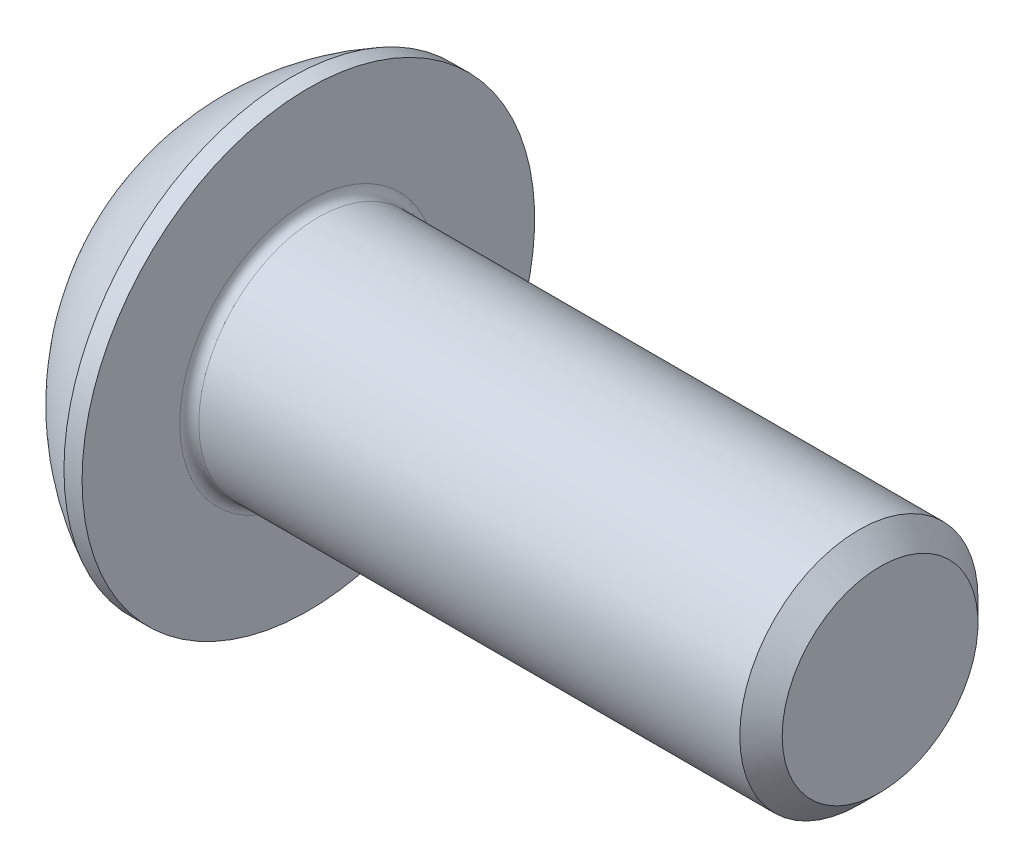
SolidWorks part; units mm, degrees
ref_plane "Plane1" through (0, 0, 0) normal (0, 0, 1) x (1, 0, 0)
ref_plane "Plane2" through (0, 0, 0) normal (0, 1, 0) x (1, 0, 0)
ref_plane "Plane3" through (0, 0, 0) normal (1, 0, 0) x (0, 0, -1)
other "Configuration Table"
sketch "BodySke" plane through (0, 0, 0) normal (0, 0, 1) x (1, 0, 0)
  line L0 (14.75, 0) -> (14.75, 2.055)
  line L1 (14.305, 2.5) -> (2.75, 2.5)
  line L2 (2.75, 2.5) -> (2.75, 4.75)
  line L3 (2.75, 4.75) -> (2.37, 4.75)
  line L4 (0, 0) -> (101.6, 0) construction
  line L5 (2.75, -4.75) -> (2.37, -4.75) construction
  line L6 (55.6768, -2.5) -> (2.75, -2.5) construction
  line L7 (14.75, 0) -> (0, 0)
  line L8 (0, 2.375) -> (0, -2.375) construction
  line L9 (0, 0) -> (0, 2.375)
  line L10 (14.75, 2.055) -> (14.305, 2.5)
  line L11 (14.75, -2.055) -> (14.305, -2.5) construction
  line L12 (3.55, 9.525) -> (3.55, -2.5) construction
  line L13 (2.75, 9.525) -> (2.75, -2.5) construction
  arc A1 (0, 2.375) -> (2.37, 4.75) centre (4.755, 0) cw
  dimension "Length" = 12
  dimension "Head_side_ht" = 0.38
  dimension "Body_ch_ang" = 45
  dimension "Thread_nom" = 12
revolve "BaseBody" add sketch "BodySke" angle 360 about L4
cosmetic thread "ThreadCosmetic" [suppressed] parameters "Thread_length"=10.4, "Thread_minor"=4.11
fillet "Fillet1" radius 0.2 1 edges at (2.75, 0, 2.5)
sketch "Sketch2" plane through (0, 0, 0) normal (0, 0, 1) x (1, 0, 0)
  line L0 (0, 1.5) -> (1.56, 1.5)
  line L1 (1.56, 1.5) -> (2.426, 0)
  line L3 (2.426, 0) -> (0, 0)
  line L4 (0, 0) -> (0, 1.5)
  line L5 (0, -1.5) -> (1.56, -1.5) construction
  line L6 (0, 0) -> (47.625, 0) construction
  dimension "D2" = 60
  dimension "PreBroach_depth" = 1.56
  dimension "PreBroach_dia" = 3
revolve "PreBroach" cut sketch "Sketch2" angle 360 about L6
sketch "Sketch3" plane through (0, 0, 0) normal (1, 0, 0) x (0, 0, -1)
  line L0 (-1.5, -0.866) -> (-1.5, 0.866)
  line L1 (-1.5, 0.866) -> (0, 1.7321)
  line L2 (0, 1.7321) -> (1.5, 0.866)
  line L3 (1.5, 0.866) -> (1.5, -0.866)
  line L4 (1.5, -0.866) -> (0, -1.7321)
  line L5 (0, -1.7321) -> (-1.5, -0.866)
  dimension "D1" = 1.5
  dimension "D2" = 1.5
extrude "Hex" cut sketch "Sketch3" along normal blind 1.56
sketch "ThdSchSke" plane through (0, 0, 0) normal (0, 0, 1) x (1, 0, 0)
  line L0 (4.35, -2.055) -> (4.0384, -2.5)
  line L1 (4.35, -2.055) -> (4.6616, -2.5)
  line L2 (4.6616, -2.5) -> (4.6616, -3.125)
  line L3 (-3.175, 0) -> (5.1513, 0) construction
  line L5 (4.6616, -3.125) -> (4.0384, -3.125)
  line L6 (4.0384, -3.125) -> (4.0384, -2.5)
  dimension "SideAngle" = 55
  dimension "VeeAngle" = 70
revolve "ThreadSchematic" [suppressed] cut sketch "ThdSchSke" angle 360 about L3
pattern_linear "ThdSchPat" [suppressed]
equation "\"D1@BodySke\" = \"Head_dia@BodySke\" * .5"
equation "\"Thread_minor@ThreadCosmetic\" = \"Minor_dia@BodySke\""
equation "\"D1@Sketch3\" = \"Hex_size@Sketch3\" / 2"
equation "\"D2@Sketch3\" = \"D1@Sketch3\""
equation "\"D3@Sketch3\" = \"Hex_size@Sketch3\""
equation "\"Thread_length@ThreadCosmetic\" = ((sgn( (\"Length@BodySke\" - \"Advance@BodySke\" * 2.0) - \"Thread_nom@BodySke\" )-1)*( (\"Length@BodySke\" - \"Advance@BodySke\" * 2.0) - \"Thread_nom@BodySke\" ))/-2+ \"Thread_nom@BodySke\""
equation "\"Thread_minor@ThdSchSke\" = \"Minor_dia@BodySke\""
equation "\"Diameter@ThdSchSke\" = \"Diameter@BodySke\""
equation "\"Overcut@ThdSchSke\" = \"Diameter@BodySke\" * 1.25"
equation "\"Start@ThdSchSke\" = \"Head_ht@BodySke\" + \"Length@BodySke\" - \"Thread_length@ThreadCosmetic\"  '---Non-countersunk---"
equation "\"Num_threads@ThdSchPat\" = int( \"Thread_length@ThreadCosmetic\" / \"Advance@BodySke\" + 0.999 )  + 1"
equation "\"Advance@ThdSchPat\" = \"Thread_length@ThreadCosmetic\" /  (\"Num_threads@ThdSchPat\" - 1) 'relax it"
equation "\"Num_threads@ThdSchPat\" = \"Num_threads@ThdSchPat\" - sgn( \"Num_threads@ThdSchPat\" - 1) '---chamfered tips only---"
